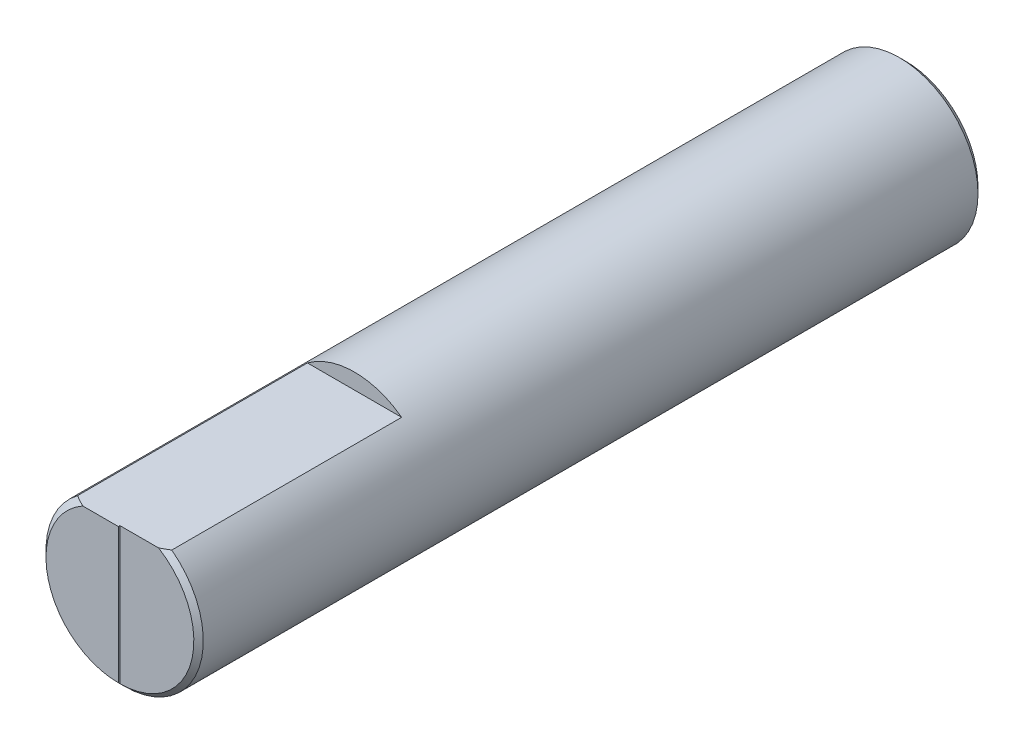
SolidWorks part; units mm, degrees
material "AISI 316 Stainless Steel Sheet (SS)"
ref_plane "Front Plane" through (0, 0, 0) normal (0, 0, 1) x (1, 0, 0)
ref_plane "Top Plane" through (0, 0, 0) normal (0, 1, 0) x (1, 0, 0)
ref_plane "Right Plane" through (0, 0, 0) normal (1, 0, 0) x (0, 0, -1)
sketch "Sketch1" plane through (0, 0, 0) normal (0, 0, 1) x (1, 0, 0)
  circle A0 centre (0, 0) radius 6.3436
  dimension "D1" = 12.6873
extrude "Main ShaftBoss-Extrude1" add sketch "Sketch1" along normal blind 63.5
sketch "Sketch2" plane through (0, 0, 63.5) normal (0, 0, 1) x (1, 0, 0)
  line L0 (0, 0) -> (0, 8.9611) construction
  line L2 (-4.699, 8.255) -> (4.699, 8.255)
  line L3 (-4.699, 8.255) -> (-4.699, 5.08)
  line L4 (-4.699, 5.08) -> (4.699, 5.08)
  line L5 (4.699, 8.255) -> (4.699, 5.08)
  line L6 (-4.699, 8.255) -> (4.699, 5.08) construction
  line L7 (-4.699, 5.08) -> (4.699, 8.255) construction
  point P3 (0, 6.6675)
  dimension "D1" = 5.08
  dimension "D2" = 3.175
  dimension "D3" = 9.398
extrude "Shaft FlatCut-Extrude1" cut sketch "Sketch2" against normal blind 19.05
chamfer "Chamfer1" distance 0.508 angle 45 2 edges at (6.3436, 0, 0) (0, -6.3436, 63.5)
sketch "Sketch3" plane through (0, 0, 63.5) normal (0, 0, 1) x (1, 0, 0)
  line L0 (0, -7.0116) -> (0, 6.7732)
  line L1 (0, 6.7732) -> (7.3584, 6.7732)
  line L2 (7.3584, 6.7732) -> (7.3584, -7.0116)
  line L3 (7.3584, -7.0116) -> (0, -7.0116)
  dimension "D1" = 7.3584
  dimension "D2" = 13.7848
  dimension "D3" = 6.7732
extrude "FaceTargetCut-Extrude2" cut sketch "Sketch3" against normal blind 0.127
